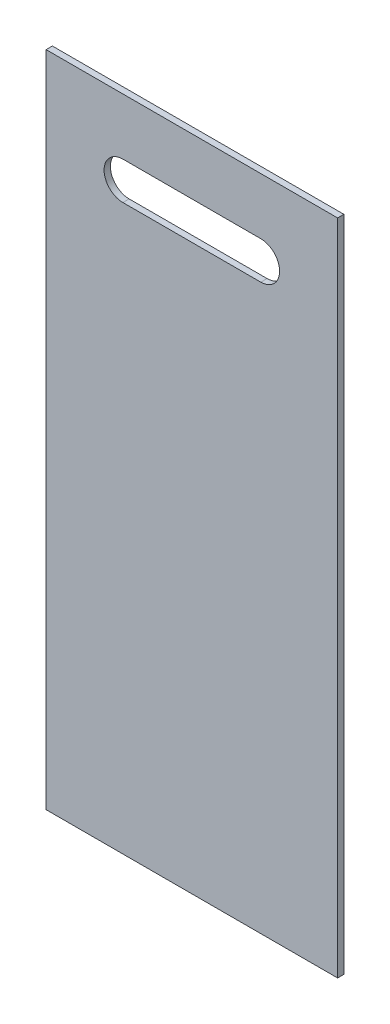
SolidWorks part; units mm, degrees
ref_plane "前视基准面" through (0, 0, 0) normal (0, 0, 1) x (1, 0, 0)
ref_plane "上视基准面" through (0, 0, 0) normal (0, 1, 0) x (1, 0, 0)
ref_plane "右视基准面" through (0, 0, 0) normal (1, 0, 0) x (0, 0, -1)
sketch "草图1" plane through (0, 0, 0) normal (0, 0, 1) x (1, 0, 0)
  line L0 (-55, 202.5) -> (55, 202.5) construction
  line L1 (-116.25, -262.5) -> (116.25, -262.5)
  line L2 (-116.25, -262.5) -> (-116.25, 262.5)
  line L3 (-116.25, 262.5) -> (116.25, 262.5)
  line L4 (116.25, -262.5) -> (116.25, 262.5)
  line L5 (-116.25, -262.5) -> (116.25, 262.5) construction
  line L6 (-116.25, 262.5) -> (116.25, -262.5) construction
  line L7 (-55, 217.5) -> (55, 217.5)
  line L8 (-55, 187.5) -> (55, 187.5)
  arc A0 (-55, 217.5) -> (-55, 187.5) centre (-55, 202.5) ccw
  arc A1 (55, 187.5) -> (55, 217.5) centre (55, 202.5) ccw
  point P0 (0, 0)
  point P8 (0, 202.5)
  dimension "D5" = 15
  dimension "D1" = 525
  dimension "D2" = 232.5
  dimension "D3" = 110
  dimension "D4" = 60
extrude "凸台-拉伸1" add sketch "草图1" along normal blind 5
